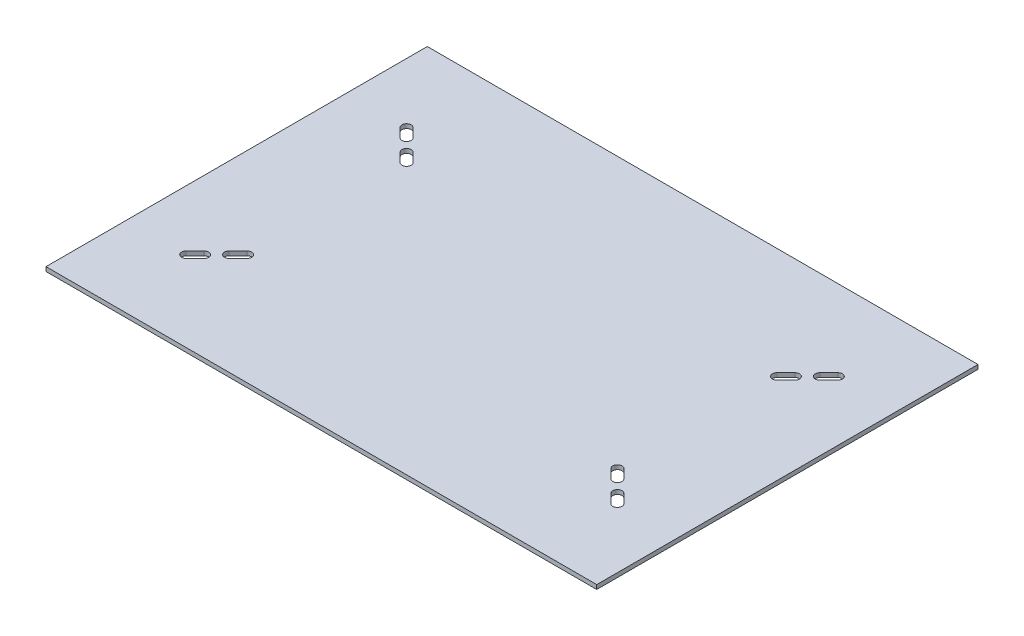
SolidWorks part; units mm, degrees
ref_plane "Front Plane" through (0, 0, 0) normal (0, 0, 1) x (1, 0, 0)
ref_plane "Top Plane" through (0, 0, 0) normal (0, 1, 0) x (1, 0, 0)
ref_plane "Right Plane" through (0, 0, 0) normal (1, 0, 0) x (0, 0, -1)
sketch "Sketch1" plane through (0, 0, 0) normal (0, 1, 0) x (1, 0, 0)
  line L1 (0, 0) -> (330.2, 0)
  line L2 (0, 0) -> (0, -228.6)
  line L3 (0, -228.6) -> (330.2, -228.6)
  line L4 (330.2, 0) -> (330.2, -228.6)
  dimension "D1" = 330.2
  dimension "D2" = 228.6
extrude "base plate" add sketch "Sketch1" against normal blind 2.54
sketch "center lines" plane through (0, 0, 0) normal (0, 1, 0) x (1, 0, 0)
  line L0 (165.1, 0) -> (165.1, -228.6) construction
  line L1 (330.2, 0) -> (0, 0) construction
  line L2 (0, -228.6) -> (330.2, -228.6) construction
  line L3 (0, -114.3) -> (330.2, -114.3) construction
  line L4 (0, 0) -> (0, -228.6) construction
  line L5 (330.2, -228.6) -> (330.2, 0) construction
sketch "Sketch3" plane through (0, 0, 0) normal (0, 1, 0) x (1, 0, 0)
  line L0 (26.0701, -177.8) -> (37.7444, -189.4743)
  line L1 (37.7444, -189.4743) -> (64.6852, -162.5336)
  line L2 (64.6852, -162.5336) -> (53.0108, -150.8592)
  line L3 (53.0108, -150.8592) -> (26.0701, -177.8)
  line L4 (35.8274, -180.3732) -> (41.2156, -174.985) construction
  line L5 (33.8829, -178.4286) -> (39.271, -173.0405)
  line L6 (37.772, -182.3177) -> (43.1601, -176.9296)
  line L7 (0, -228.6) -> (330.2, -228.6) construction
  line L8 (54.0849, -162.1157) -> (48.6968, -167.5038) construction
  line L9 (56.0295, -164.0602) -> (50.6413, -169.4484)
  line L10 (165.1, 0) -> (165.1, -228.6) construction
  line L11 (0, -114.3) -> (330.2, -114.3) construction
  line L12 (64.6852, -66.0664) -> (53.0108, -77.7408)
  line L13 (37.7444, -39.1257) -> (64.6852, -66.0664)
  line L14 (26.0701, -50.8) -> (37.7444, -39.1257)
  line L15 (53.0108, -77.7408) -> (26.0701, -50.8)
  line L16 (292.4556, -39.1257) -> (265.5148, -66.0664)
  line L17 (304.1299, -50.8) -> (292.4556, -39.1257)
  line L18 (277.1892, -77.7408) -> (304.1299, -50.8)
  line L19 (265.5148, -66.0664) -> (277.1892, -77.7408)
  line L20 (265.5148, -162.5336) -> (277.1892, -150.8592)
  line L21 (292.4556, -189.4743) -> (265.5148, -162.5336)
  line L22 (304.1299, -177.8) -> (292.4556, -189.4743)
  line L23 (277.1892, -150.8592) -> (304.1299, -177.8)
  line L24 (52.1404, -160.1711) -> (46.7522, -165.5593)
  line L25 (35.8274, -48.2268) -> (41.2156, -53.615) construction
  line L26 (33.8829, -50.1714) -> (39.271, -55.5595)
  line L27 (37.772, -46.2823) -> (43.1601, -51.6704)
  line L28 (54.0849, -66.4843) -> (48.6968, -61.0962) construction
  line L29 (56.0295, -64.5398) -> (50.6413, -59.1516)
  line L30 (52.1404, -68.4289) -> (46.7522, -63.0407)
  line L31 (294.3726, -48.2268) -> (288.9844, -53.615) construction
  line L32 (296.3171, -50.1714) -> (290.929, -55.5595)
  line L33 (292.428, -46.2823) -> (287.0399, -51.6704)
  line L34 (276.1151, -66.4843) -> (281.5032, -61.0962) construction
  line L35 (274.1705, -64.5398) -> (279.5587, -59.1516)
  line L36 (278.0596, -68.4289) -> (283.4478, -63.0407)
  line L37 (276.1151, -162.1157) -> (281.5032, -167.5038) construction
  line L38 (274.1705, -164.0602) -> (279.5587, -169.4484)
  line L39 (278.0596, -160.1711) -> (283.4478, -165.5593)
  line L40 (294.3726, -180.3732) -> (288.9844, -174.985) construction
  line L41 (296.3171, -178.4286) -> (290.929, -173.0405)
  line L42 (292.428, -182.3177) -> (287.0399, -176.9296)
  arc A0 (33.8829, -178.4286) -> (37.772, -182.3177) centre (35.8274, -180.3732) ccw
  arc A1 (43.1601, -176.9296) -> (39.271, -173.0405) centre (41.2156, -174.985) ccw
  arc A2 (56.0295, -164.0602) -> (52.1404, -160.1711) centre (54.0849, -162.1157) ccw
  arc A3 (46.7522, -165.5593) -> (50.6413, -169.4484) centre (48.6968, -167.5038) ccw
  arc A4 (33.8829, -50.1714) -> (37.772, -46.2823) centre (35.8274, -48.2268) cw
  arc A5 (43.1601, -51.6704) -> (39.271, -55.5595) centre (41.2156, -53.615) cw
  arc A6 (56.0295, -64.5398) -> (52.1404, -68.4289) centre (54.0849, -66.4843) cw
  arc A7 (46.7522, -63.0407) -> (50.6413, -59.1516) centre (48.6968, -61.0962) cw
  arc A8 (296.3171, -50.1714) -> (292.428, -46.2823) centre (294.3726, -48.2268) ccw
  arc A9 (287.0399, -51.6704) -> (290.929, -55.5595) centre (288.9844, -53.615) ccw
  arc A10 (274.1705, -64.5398) -> (278.0596, -68.4289) centre (276.1151, -66.4843) ccw
  arc A11 (283.4478, -63.0407) -> (279.5587, -59.1516) centre (281.5032, -61.0962) ccw
  arc A12 (274.1705, -164.0602) -> (278.0596, -160.1711) centre (276.1151, -162.1157) cw
  arc A13 (283.4478, -165.5593) -> (279.5587, -169.4484) centre (281.5032, -167.5038) cw
  arc A14 (296.3171, -178.4286) -> (292.428, -182.3177) centre (294.3726, -180.3732) cw
  arc A15 (287.0399, -176.9296) -> (290.929, -173.0405) centre (288.9844, -174.985) cw
  point P8 (31.9072, -183.6372)
  point P29 (38.5215, -177.6791)
  point P36 (51.3909, -164.8097)
  point P41 (54.6203, -161.5516)
  point P44 (38.5215, -50.9209)
  point P51 (51.3909, -63.7903)
  point P58 (291.6785, -50.9209)
  point P65 (278.8091, -63.7903)
  point P72 (278.8091, -164.8097)
  point P79 (291.6785, -177.6791)
  point P84 (43.1601, -173.0405)
  point P85 (46.7522, -169.4484)
  dimension "D6" = 2.75
  dimension "D10" = 5.08
  dimension "D1" = 38.1
  dimension "D2" = 16.51
  dimension "D3" = 45
  dimension "D4" = 63.5
  dimension "D5" = 127.3556
  dimension "D7" = 7.62
  dimension "D8" = 5.08
  dimension "D9" = 2.286
extrude "Cut-Extrude9" cut sketch "Sketch3" against normal through all contours A5 L27 A4 L26 | L33 A9 L32 A8 | L36 A11 L35 A10 | A13 L39 A12 L38 | A15 L42 A14 L41 | L6 A1 L5 A0 | L24 A3 L9 A2 | L30 A7 L29 A6
